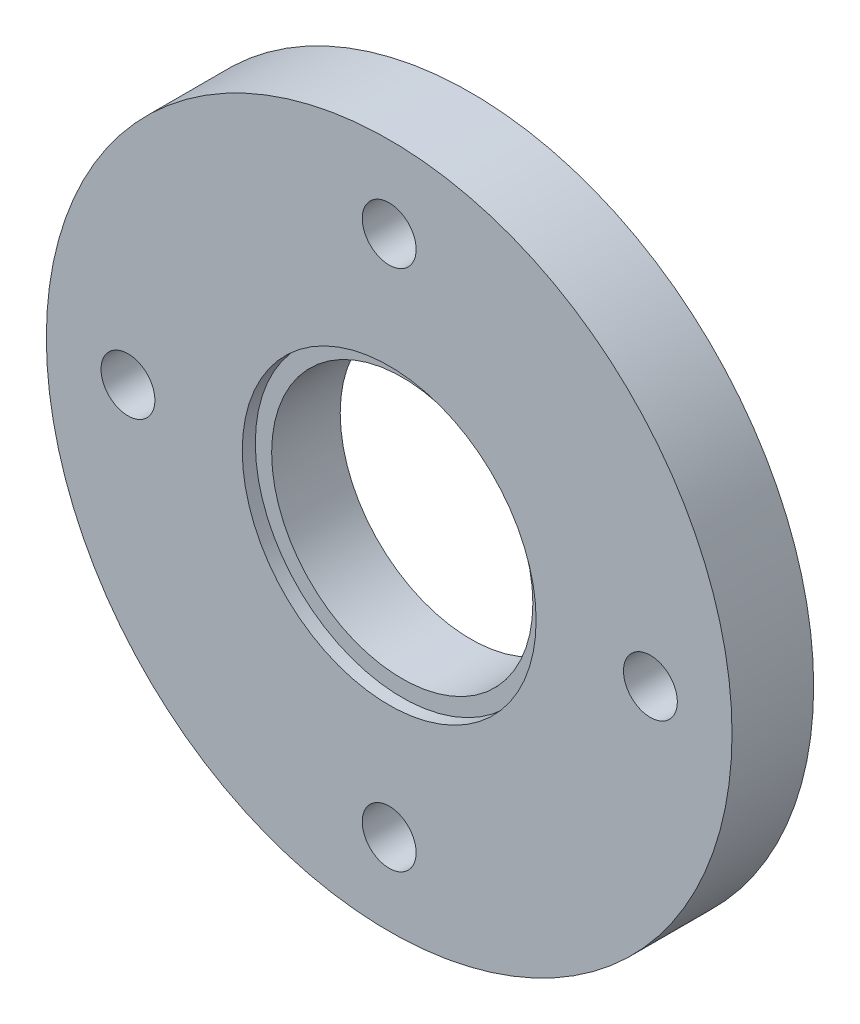
SolidWorks part; units mm, degrees
ref_plane "Спереди" through (0, 0, 0) normal (0, 0, 1) x (1, 0, 0)
ref_plane "Сверху" through (0, 0, 0) normal (0, 1, 0) x (1, 0, 0)
ref_plane "Справа" through (0, 0, 0) normal (1, 0, 0) x (0, 0, -1)
sketch "Эскиз1" plane through (0, 0, 0) normal (0, 0, 1) x (1, 0, 0)
  line L0 (0, 21) -> (0, -21) construction
  line L1 (-21, 0) -> (21, 0) construction
  circle A0 centre (0, 0) radius 21
  circle A1 centre (0, 0) radius 8
  circle A2 centre (0, 0) radius 16 construction
  dimension "D1" = 42
  dimension "D2" = 16
  dimension "D3" = 32
extrude "Бобышка-Вытянуть1" add sketch "Эскиз1" along normal blind 5
hole_wizard "Отверстие обработанное метчиком M4x0.71" positions "Эскиз3" profile "Эскиз2" tap size "M4x0.7" standard "Ansi Metric" end condition through all
sketch "Эскиз3" plane through (0, 0, 5) normal (0, 0, 1) x (1, 0, 0)
  line L0 (0, 21) -> (0, -21) construction
  line L1 (-21, 0) -> (21, 0) construction
  circle A0 centre (0, 0) radius 16 construction
  point P2 (0, 16)
  point P8 (-16, 0)
  point P12 (0, -16)
  point P14 (16, 0)
sketch "Эскиз2" plane through (0, 16, 5) normal (1, 0, 0) x (0, -1, 0)
  line L0 (0, 0) -> (0, 5)
  line L1 (0, 5) -> (1.65, 5)
  line L2 (1.65, 5) -> (1.65, 0)
  line L5 (1.65, 0) -> (0, 0)
  line L11 (0, -6.35) -> (0, 107.95) construction
  dimension "Диаметр проходного сверла" = 3.3
  dimension "Глубина проходного сверла" = 5
cosmetic thread "Отверстие резьбы1" parameters "D2"=4
cosmetic thread "Отверстие резьбы2" parameters "D2"=4
cosmetic thread "Отверстие резьбы3" parameters "D2"=4
cosmetic thread "Отверстие резьбы4" parameters "D2"=4
sketch "Эскиз4" plane through (0, 0, 5) normal (0, 0, 1) x (1, 0, 0)
  circle A0 centre (0, 0) radius 9
  dimension "D1" = 18
extrude "Вырез-Вытянуть1" cut sketch "Эскиз4" against normal blind 0.8
